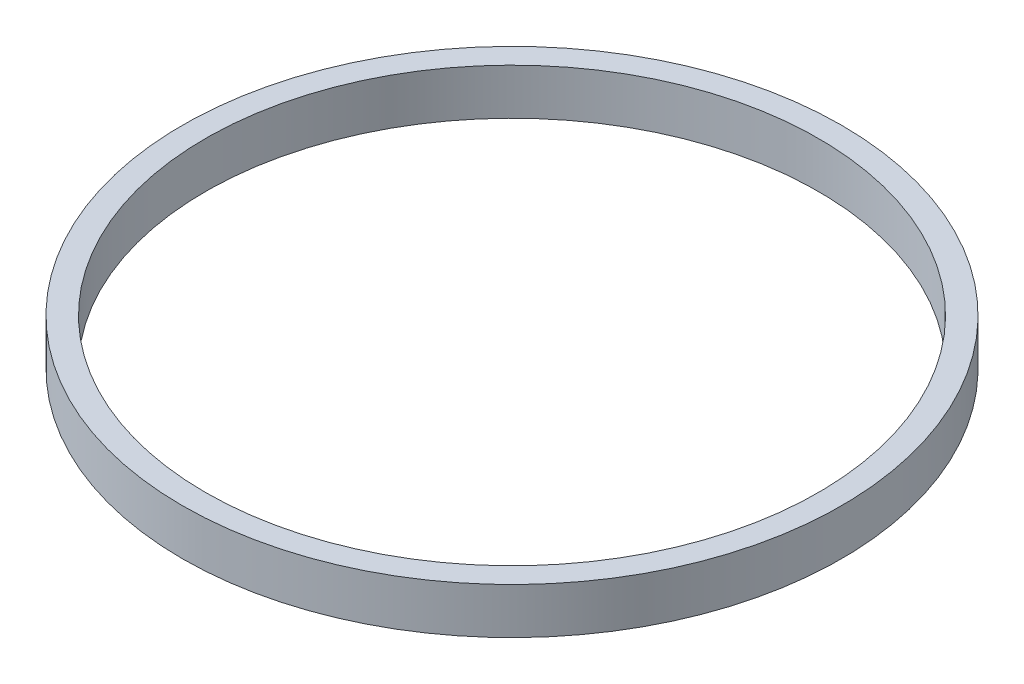
SolidWorks part; units mm, degrees
ref_plane "Спереди" through (0, 0, 0) normal (0, 0, 1) x (1, 0, 0)
ref_plane "Сверху" through (0, 0, 0) normal (0, 1, 0) x (1, 0, 0)
ref_plane "Справа" through (0, 0, 0) normal (1, 0, 0) x (0, 0, -1)
sketch "Эскиз1" plane through (0, 0, 0) normal (0, 1, 0) x (1, 0, 0)
  circle A0 centre (0, 0) radius 20
  circle A1 centre (0, 0) radius 21.5
  dimension "D1" = 40
  dimension "D2" = 43
extrude "Бобышка-Вытянуть1" add sketch "Эскиз1" along normal blind 3
